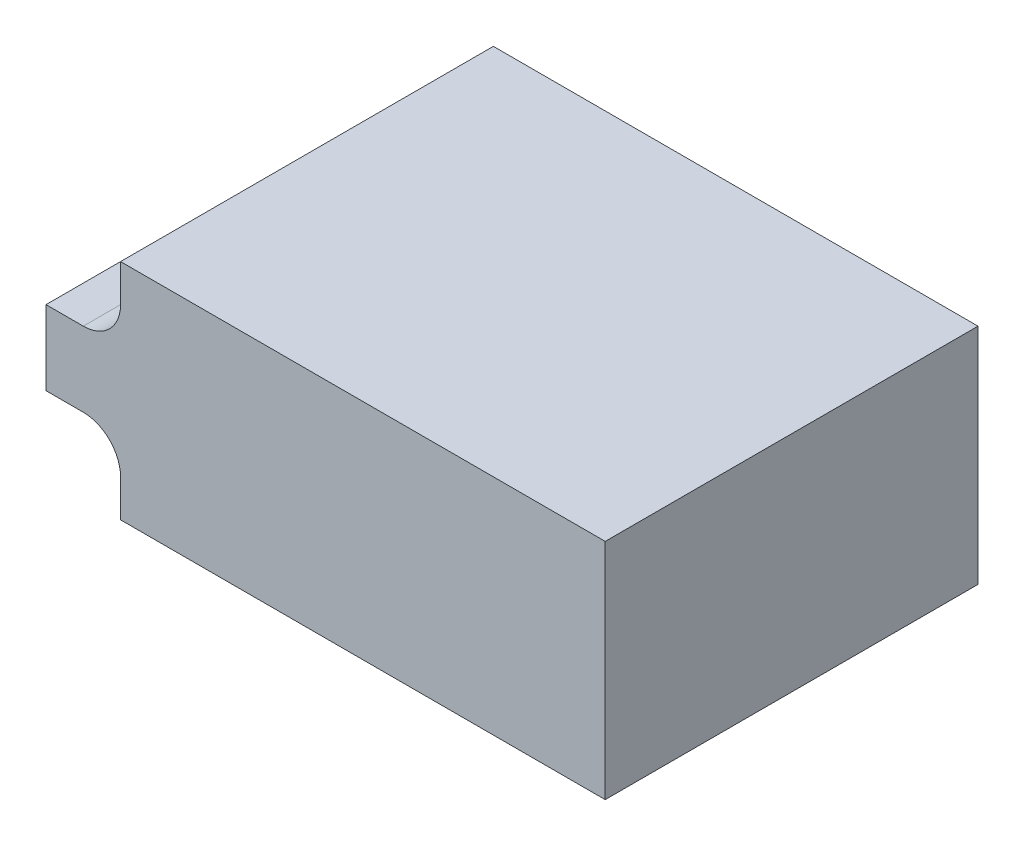
SolidWorks part; units mm, degrees
ref_plane "Plan de face" through (0, 0, 0) normal (0, 0, 1) x (1, 0, 0)
ref_plane "Plan de dessus" through (0, 0, 0) normal (0, 1, 0) x (1, 0, 0)
ref_plane "Plan de droite" through (0, 0, 0) normal (1, 0, 0) x (0, 0, -1)
sketch "Esquisse1" plane through (0, 0, 0) normal (0, 0, 1) x (1, 0, 0)
  line L1 (-7.5, 3) -> (7.5, 3)
  line L2 (-7.5, 3) -> (-7.5, -3)
  line L3 (-7.5, -3) -> (7.5, -3)
  line L4 (7.5, 3) -> (7.5, -3)
  line L5 (-7.5, 3) -> (7.5, -3) construction
  line L6 (-7.5, -3) -> (7.5, 3) construction
  point P0 (0, 0)
  dimension "D1" = 15
  dimension "D2" = 6
extrude "Boss.-Extru.1" add sketch "Esquisse1" along normal blind 10
sketch "Esquisse2" plane through (0, 0, 0) normal (0, 0, -1) x (-1, 0, 0)
  line L0 (5.5, -1) -> (5.5, 1) construction
  line L1 (7.5, 3) -> (5.5, 3)
  line L2 (7.5, 3) -> (7.5, 1)
  line L3 (7.5, 1) -> (5.5, 1)
  line L4 (5.5, 3) -> (5.5, 1)
  line L5 (7.5, -3) -> (5.5, -3)
  line L6 (7.5, -3) -> (7.5, -1)
  line L7 (7.5, -1) -> (5.5, -1)
  line L8 (5.5, -3) -> (5.5, -1)
  dimension "D1" = 2
  dimension "D2" = 2
  dimension "D3" = 2
extrude "Enlèv. mat.-Extru.1" cut sketch "Esquisse2" against normal through all
fillet "Congé1" radius 1 2 edges at (-5.5, -1, 5) (-5.5, 1, 5)
